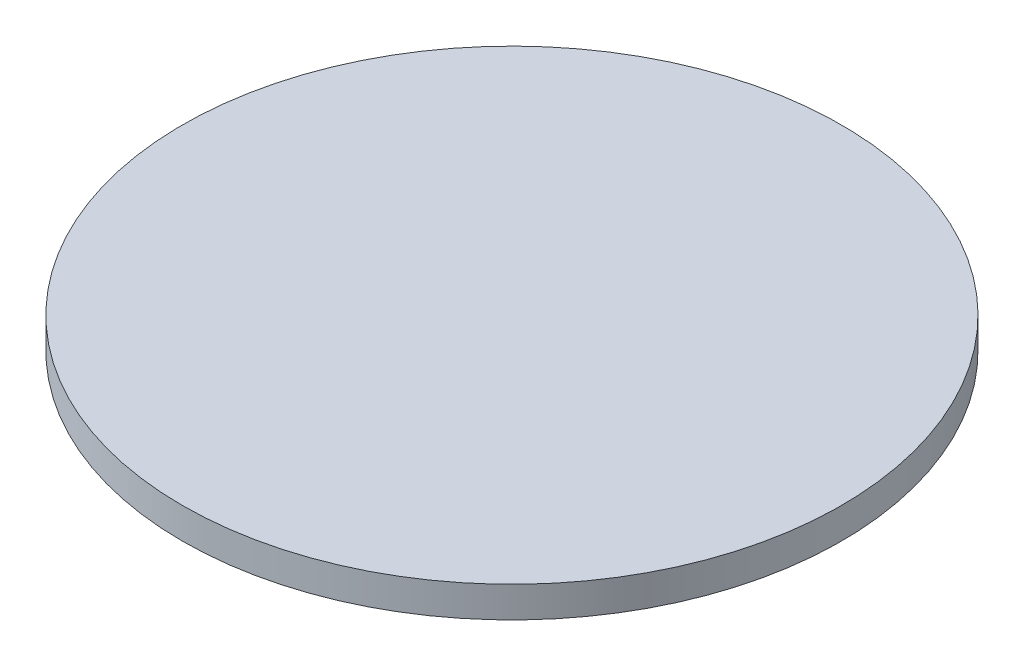
SolidWorks part; units mm, degrees
ref_plane "Front Plane" through (0, 0, 0) normal (0, 0, 1) x (1, 0, 0)
ref_plane "Top Plane" through (0, 0, 0) normal (0, 1, 0) x (1, 0, 0)
ref_plane "Right Plane" through (0, 0, 0) normal (1, 0, 0) x (0, 0, -1)
sketch "Sketch1" plane through (0, 0, 0) normal (0, 1, 0) x (1, 0, 0)
  circle A0 centre (0, 0) radius 64
  dimension "D1" = 128
extrude "Boss-Extrude1" add sketch "Sketch1" along normal blind 6
sketch "Sketch2" plane through (0, 0, 0) normal (0, -1, 0) x (1, 0, 0)
  circle A0 centre (0, 0) radius 7.25
  dimension "D1" = 14.5
extrude "Boss-Extrude2" add sketch "Sketch2" along normal blind 20
sketch "Sketch3" plane through (0, -20, 0) normal (0, -1, 0) x (1, 0, 0)
  circle A0 centre (0, 0) radius 5
  dimension "D1" = 10
extrude "Boss-Extrude3" add sketch "Sketch3" along normal blind 15
sketch "Sketch4" plane through (0, 0, 0) normal (1, 0, 0) x (0, 0, -1)
  line L0 (0, 16.9876) -> (0, -52.019) construction
  line L1 (-5, -35) -> (5, -35) construction
  circle A0 centre (0, -31) radius 1.9
  circle A1 centre (0, -24) radius 1.9
  dimension "D1" = 3.8
  dimension "D2" = 3.8
  dimension "D3" = 4
  dimension "D4" = 7
extrude "Cut-Extrude1" cut sketch "Sketch4" along normal mid plane 20
